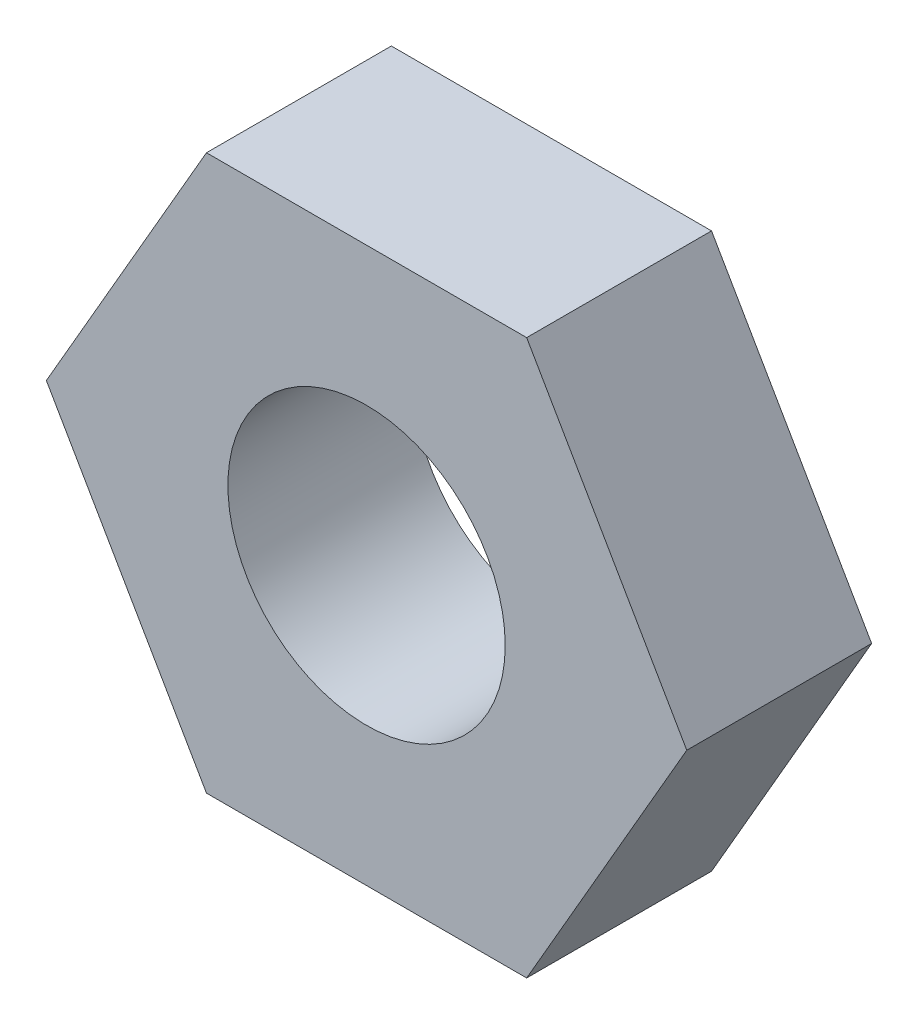
SolidWorks part; units mm, degrees
ref_plane "前视基准面" through (0, 0, 0) normal (0, 0, 1) x (1, 0, 0)
ref_plane "上视基准面" through (0, 0, 0) normal (0, 1, 0) x (1, 0, 0)
ref_plane "右视基准面" through (0, 0, 0) normal (1, 0, 0) x (0, 0, -1)
other "Configuration Table"
sketch "草图1" plane through (0, 0, 0) normal (0, 0, 1) x (1, 0, 0)
  line L1 (3.4641, 0) -> (1.7321, 3)
  line L2 (1.7321, 3) -> (-1.7321, 3)
  line L3 (-1.7321, 3) -> (-3.4641, 0)
  line L4 (-3.4641, 0) -> (-1.7321, -3)
  line L5 (-1.7321, -3) -> (1.7321, -3)
  line L6 (1.7321, -3) -> (3.4641, 0)
  circle A0 centre (0, 0) radius 3 construction
  circle A1 centre (0, 0) radius 1.5
  dimension "D2" = 3
  dimension "D1" = 6
extrude "凸台-拉伸1" add sketch "草图1" along normal blind 2
